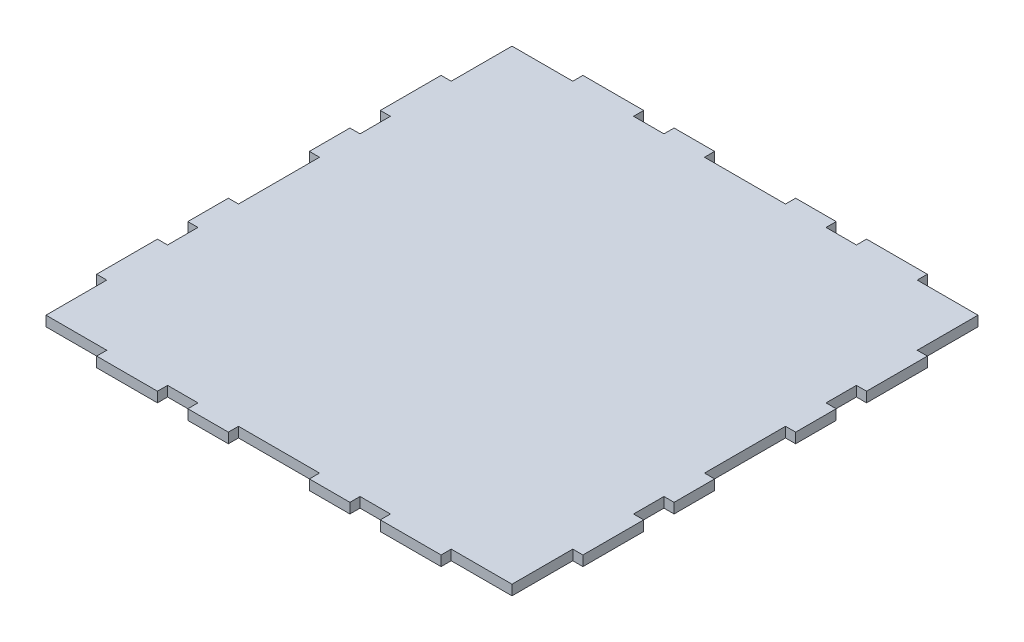
SolidWorks part; units mm, degrees
ref_plane "Front Plane" through (0, 0, 0) normal (0, 0, 1) x (1, 0, 0)
ref_plane "Top Plane" through (0, 0, 0) normal (0, 1, 0) x (1, 0, 0)
ref_plane "Right Plane" through (0, 0, 0) normal (1, 0, 0) x (0, 0, -1)
sketch "Sketch2" plane through (0, 0, 0) normal (0, 1, 0) x (1, 0, 0)
  line L0 (146.05, 0) -> (146.05, 292.1)
  line L1 (0, 0) -> (292.1, 0)
  line L2 (0, 0) -> (0, 292.1)
  line L3 (0, 292.1) -> (292.1, 292.1)
  line L4 (292.1, 0) -> (292.1, 292.1)
  line L5 (95.25, 0) -> (120.65, 0)
  line L6 (95.25, 0) -> (95.25, -6.35)
  line L7 (95.25, -6.35) -> (120.65, -6.35)
  line L8 (120.65, 0) -> (120.65, -6.35)
  line L9 (38.1, 0) -> (76.2, 0)
  line L10 (38.1, 0) -> (38.1, -6.35)
  line L11 (38.1, -6.35) -> (76.2, -6.35)
  line L12 (76.2, 0) -> (76.2, -6.35)
  line L13 (0, 146.05) -> (292.1, 146.05)
  line L14 (0, 0) -> (292.1, 292.1)
  line L15 (215.9, 0) -> (215.9, -6.35)
  line L16 (254, -6.35) -> (215.9, -6.35)
  line L17 (254, 0) -> (254, -6.35)
  line L18 (254, 0) -> (215.9, 0)
  line L19 (171.45, 0) -> (171.45, -6.35)
  line L20 (196.85, -6.35) -> (171.45, -6.35)
  line L21 (196.85, 0) -> (196.85, -6.35)
  line L22 (196.85, 0) -> (171.45, 0)
  line L23 (196.85, 292.1) -> (171.45, 292.1)
  line L24 (196.85, 292.1) -> (196.85, 298.45)
  line L25 (196.85, 298.45) -> (171.45, 298.45)
  line L26 (171.45, 292.1) -> (171.45, 298.45)
  line L27 (254, 292.1) -> (215.9, 292.1)
  line L28 (254, 292.1) -> (254, 298.45)
  line L29 (254, 298.45) -> (215.9, 298.45)
  line L30 (215.9, 292.1) -> (215.9, 298.45)
  line L31 (76.2, 292.1) -> (76.2, 298.45)
  line L32 (38.1, 298.45) -> (76.2, 298.45)
  line L33 (38.1, 292.1) -> (38.1, 298.45)
  line L34 (38.1, 292.1) -> (76.2, 292.1)
  line L35 (120.65, 292.1) -> (120.65, 298.45)
  line L36 (95.25, 298.45) -> (120.65, 298.45)
  line L37 (95.25, 292.1) -> (95.25, 298.45)
  line L38 (95.25, 292.1) -> (120.65, 292.1)
  line L39 (292.1, 95.25) -> (292.1, 120.65)
  line L40 (292.1, 95.25) -> (298.45, 95.25)
  line L41 (298.45, 95.25) -> (298.45, 120.65)
  line L42 (292.1, 120.65) -> (298.45, 120.65)
  line L43 (292.1, 38.1) -> (292.1, 76.2)
  line L44 (292.1, 38.1) -> (298.45, 38.1)
  line L45 (298.45, 38.1) -> (298.45, 76.2)
  line L46 (292.1, 76.2) -> (298.45, 76.2)
  line L47 (292.1, 215.9) -> (298.45, 215.9)
  line L48 (298.45, 254) -> (298.45, 215.9)
  line L49 (292.1, 254) -> (298.45, 254)
  line L50 (292.1, 254) -> (292.1, 215.9)
  line L51 (292.1, 171.45) -> (298.45, 171.45)
  line L52 (298.45, 196.85) -> (298.45, 171.45)
  line L53 (292.1, 196.85) -> (298.45, 196.85)
  line L54 (292.1, 196.85) -> (292.1, 171.45)
  line L55 (0, 196.85) -> (0, 171.45)
  line L56 (0, 196.85) -> (-6.35, 196.85)
  line L57 (-6.35, 196.85) -> (-6.35, 171.45)
  line L58 (0, 171.45) -> (-6.35, 171.45)
  line L59 (0, 254) -> (0, 215.9)
  line L60 (0, 254) -> (-6.35, 254)
  line L61 (-6.35, 254) -> (-6.35, 215.9)
  line L62 (0, 215.9) -> (-6.35, 215.9)
  line L63 (0, 76.2) -> (-6.35, 76.2)
  line L64 (-6.35, 38.1) -> (-6.35, 76.2)
  line L65 (0, 38.1) -> (-6.35, 38.1)
  line L66 (0, 38.1) -> (0, 76.2)
  line L67 (0, 120.65) -> (-6.35, 120.65)
  line L68 (-6.35, 95.25) -> (-6.35, 120.65)
  line L69 (0, 95.25) -> (-6.35, 95.25)
  line L70 (0, 95.25) -> (0, 120.65)
  dimension "D1" = 292.1
  dimension "D2" = 292.1
  dimension "D3" = 6.35
  dimension "D4" = 25.4
  dimension "D5" = 95.25
  dimension "D6" = 38.1
  dimension "D7" = 6.35
  dimension "D8" = 38.1
extrude "Boss-Extrude1" add sketch "Sketch2" along normal blind 6.35 contours L12 L1 L10 L11 | L8 L1 L6 L7 | L21 L1 L19 L20 | L17 L1 L15 L16 | L46 L4 L44 L45 | L42 L4 L40 L41 | L53 L4 L51 L52 | L49 L4 L47 L48 | L30 L3 L28 L29 | L26 L3 L24 L25 | L37 L3 L35 L36 | L33 L3 L31 L32 | L62 L2 L60 L61 | L58 L2 L56 L57 | L69 L2 L67 L68 | L65 L2 L63 L64 | L2 L14 L13 | L14 L1 L0 | L13 L0 L1 L4 | L14 L13 L4 | L0 L14 L3 | L2 L13 L0 L3
